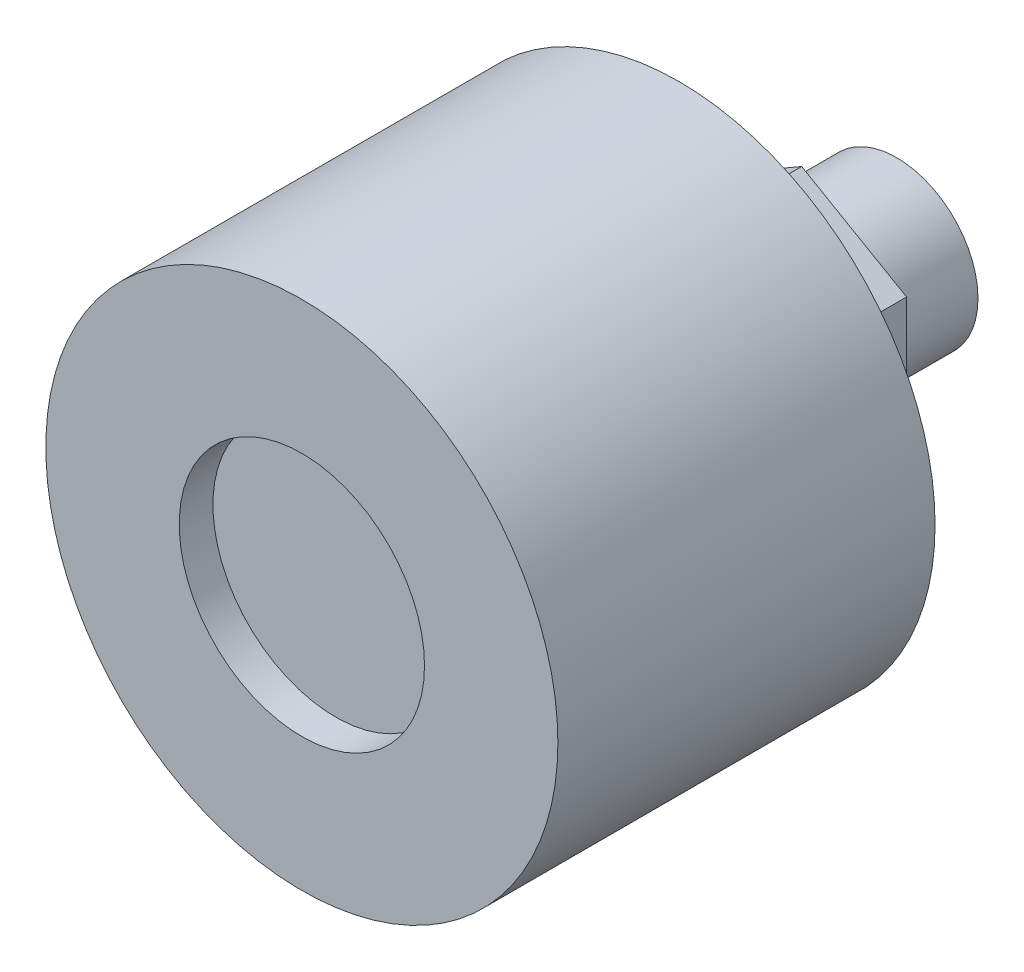
SolidWorks part; units mm, degrees
material "1060 Alloy"
ref_plane "Front Plane" through (0, 0, 0) normal (0, 0, 1) x (1, 0, 0)
ref_plane "Top Plane" through (0, 0, 0) normal (0, 1, 0) x (1, 0, 0)
ref_plane "Right Plane" through (0, 0, 0) normal (1, 0, 0) x (0, 0, -1)
sketch "Sketch3" plane through (0, 0, 0) normal (0, 0, 1) x (1, 0, 0)
  circle A0 centre (0, 0) radius 8.35
  circle A1 centre (0, 0) radius 4
  dimension "D1" = 16.7
extrude "Boss-Extrude1" add sketch "Sketch3" along normal blind 1 and the other way blind 0.1
sketch "Sketch4" plane through (0, 0, -0.1) normal (0, 0, -1) x (-1, 0, 0)
  circle A0 centre (0, 0) radius 8.35
extrude "Boss-Extrude2" add sketch "Sketch4" along normal blind 11.2
sketch "Sketch5" plane through (0, 0, -11.3) normal (0, 0, -1) x (-1, 0, 0)
  line L0 (0, -3.95) -> (0, 3.95) construction
  line L2 (0, 3.95) -> (-3.4208, 1.975)
  line L3 (-3.4208, 1.975) -> (-3.4208, -1.975)
  line L4 (-3.4208, -1.975) -> (0, -3.95)
  line L5 (0, -3.95) -> (3.4208, -1.975)
  line L6 (3.4208, -1.975) -> (3.4208, 1.975)
  line L7 (3.4208, 1.975) -> (0, 3.95)
  circle A1 centre (0, 0) radius 3.4208 construction
  point P6 (0, 0)
  point P9 (0, 3.95)
  point P13 (0, -3.95)
  dimension "D1" = 7.9
extrude "Boss-Extrude4" add sketch "Sketch5" along normal blind 4
sketch "Sketch6" plane through (0, 0, -15.3) normal (0, 0, -1) x (-1, 0, 0)
  circle A0 centre (0, 0) radius 2.65
  dimension "D1" = 5.3
extrude "Boss-Extrude5" add sketch "Sketch6" along normal blind 3.1
sketch "Sketch7" plane through (0, 0, -18.4) normal (0, 0, -1) x (-1, 0, 0)
  circle A0 centre (0, 0) radius 0.2443
extrude "Cut-Extrude1" cut sketch "Sketch7" against normal blind 2
